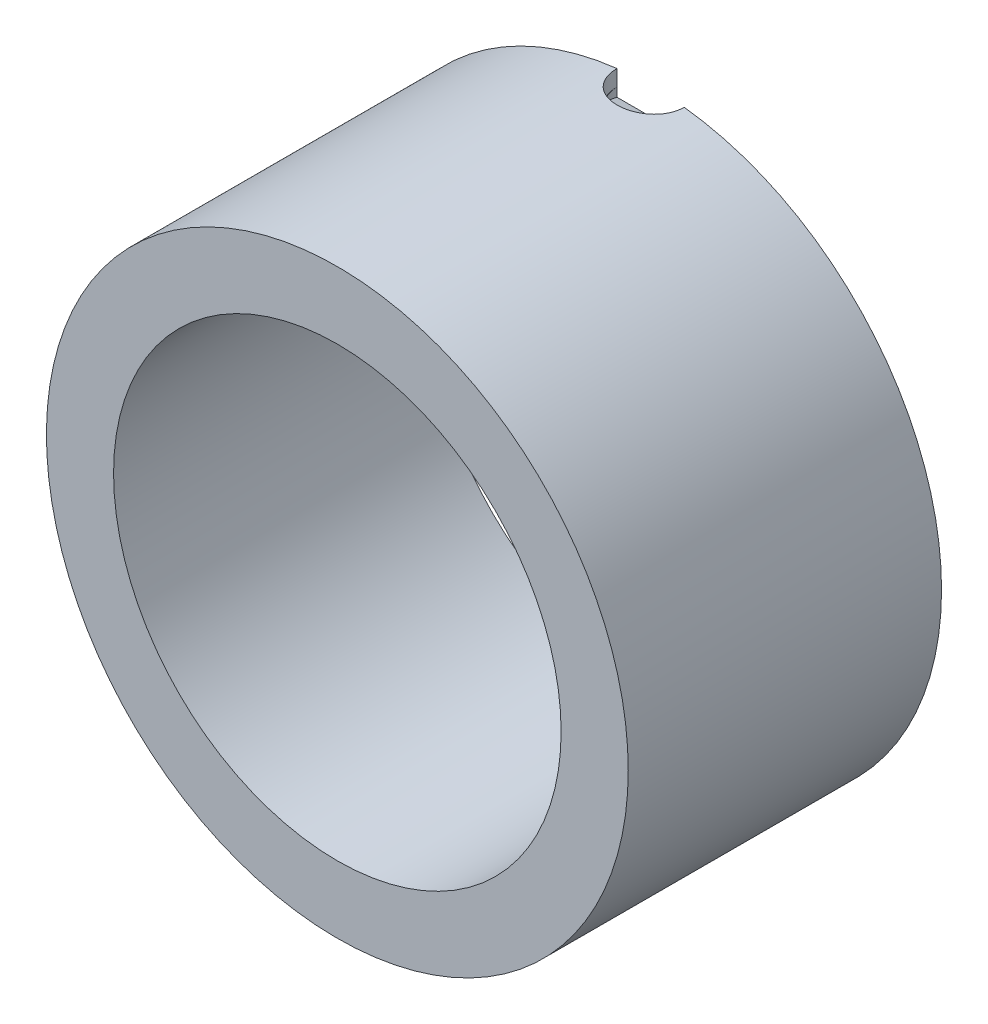
SolidWorks part; units mm, degrees
ref_plane "前视基准面" through (0, 0, 0) normal (0, 0, 1) x (1, 0, 0)
ref_plane "上视基准面" through (0, 0, 0) normal (0, 1, 0) x (1, 0, 0)
ref_plane "右视基准面" through (0, 0, 0) normal (1, 0, 0) x (0, 0, -1)
sketch "草图1" plane through (0, 0, 0) normal (0, 0, 1) x (1, 0, 0)
  circle A0 centre (0, 0) radius 200
  circle A1 centre (0, 0) radius 260
  dimension "D1" = 400
  dimension "D2" = 520
extrude "凸台-拉伸1" add sketch "草图1" along normal blind 280
ref_plane "基准面2" through (0, 260, 0) normal (0, 1, 0) x (1, 0, 0)
sketch "草图4" plane through (0, 260, 0) normal (0, 1, 0) x (1, 0, 0)
  circle A0 centre (0, 0) radius 30
extrude "切除-拉伸1" cut sketch "草图4" against normal blind 15.98
sketch "草图3" plane through (0, 0, 0) normal (1, 0, 0) x (0, 0, -1)
  line L0 (-30, 260) -> (-30, 244.0192) construction
  line L1 (-30, 260) -> (-280, 260) construction
  line L2 (-30, 244.0192) -> (0, 235.9808)
  line L3 (0, -260) -> (0, 258.2634) construction
  line L4 (-61.0827, 240) -> (49.3345, 240) construction
  line L5 (-15, 284.1835) -> (-15, 194.9741) construction
  line L6 (-30, 244.0192) -> (0, 244.0192)
  line L7 (0, 244.0192) -> (0, 235.9808)
  point P11 (-15, 240)
  point P13 (0, 0)
  point P15 (0, 0)
  dimension "D1" = 30
  dimension "D2" = 20
  dimension "D3" = 15
  dimension "D4" = 15
sketch "草图17" plane through (0, 244.02, 0) normal (0, 1, 0) x (1, 0, 0)
  line L0 (0, -30) -> (-80.4068, -30) construction
  circle A0 centre (0, 0) radius 30
ref_plane "基准面4" through (0, 244.02, 0) normal (0, 1, 0) x (1, 0, 0)
ref_plane "基准面5" through (0, 220.1738, -58.9954) normal (0, 0.9659, -0.2588) x (-1, 0, 0)
sketch "草图18" plane through (0, 220.1738, -58.9954) normal (0, 0.9659, -0.2588) x (-1, 0, 0)
  circle A0 centre (0, 62.1348) radius 30
  point P2 (0, 92.1348)
  point P5 (0, 92.1348)
  point P6 (0, 0)
  dimension "D1" = 60
extrude "切除-拉伸4" cut sketch "草图18" along normal blind 15.98
